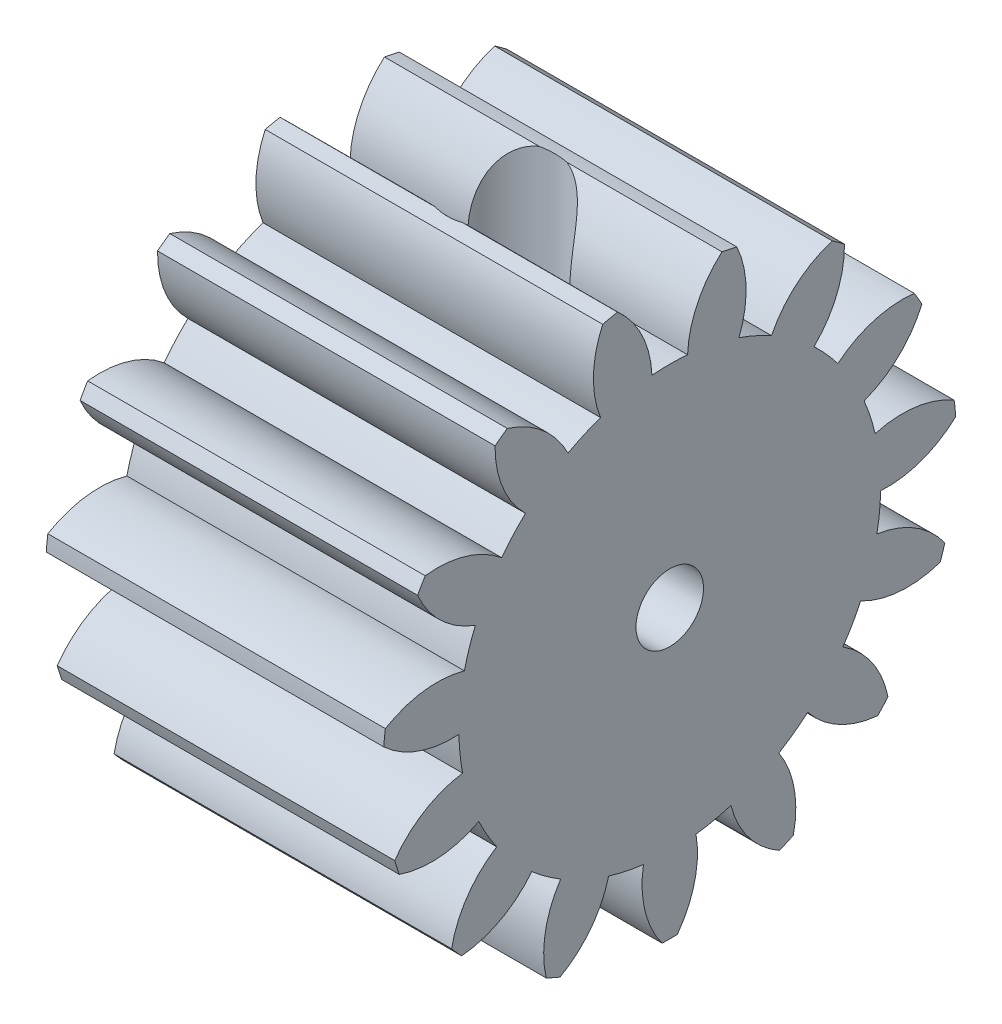
SolidWorks part; units mm, degrees
ref_plane "Plane1" through (0, 0, 0) normal (0, 0, 1) x (1, 0, 0)
ref_plane "Plane2" through (0, 0, 0) normal (0, 1, 0) x (1, 0, 0)
ref_plane "Plane3" through (0, 0, 0) normal (1, 0, 0) x (0, 0, -1)
other "Configuration Table"
sketch "HoldingSke" plane through (0, 0, 0) normal (0, 1, 0) x (1, 0, 0)
  line L0 (0, 0) -> (0.644, -0.1725)
  line L1 (-15, 0) -> (100, 0) construction
  line L2 (0, 0) -> (-2.1039, 2.3779)
  line L3 (0, 0) -> (-11.863, 4.5341)
  line L4 (0, 0) -> (8.3417, 2.2352)
  line L5 (0, 0) -> (-46.8476, -17.4728)
  line L6 (0, 0) -> (-12.4344, -8.3896)
  line L7 (-2.1039, 2.3779) -> (8.6586, 51.2059)
  line L8 (-76.2, 54.61) -> (-75.7, 54.61)
  line L9 (-71.009, 38.7566) -> (-53.1078, 45.2721)
  line L10 (-76.2, 71.12) -> (104.1128, 71.12)
  line L11 (0, 0) -> (-15, 0)
  line L12 (-76.2, 101.6) -> (-76.147, 101.6)
  line L13 (24.9733, 27.94) -> (52.9518, 28.4284)
  line L14 (24.9733, 27.94) -> (24.9743, 27.94)
  line L15 (24.9733, 27.94) -> (100.4006, 29.5858)
  line L16 (-63.627, -1.5) -> (-12.827, -1.5)
  circle A0 centre (0, 0) radius 1.5
  circle A1 centre (0, 0) radius 9.374
  circle A2 centre (0, 0) radius 37.5
  circle A3 centre (0, 0) radius 1.5
  dimension "MHD" = 18.748
  dimension "Hub_dia" = 75
  dimension "Bore" = 3
  dimension "MBD" = 3
  dimension "Num_teeth" = 15
  dimension "Pitch" = 0.6667
  dimension "Overall_len" = 50
  dimension "Show_teeth" = 15
  dimension "Thickness" = 15
  dimension "OAL" = 50.0001
  dimension "T_dim" = 0.5
  dimension "Ap" = 20
  dimension "H" = 19.05
  dimension "Pitch_radius" = 180.3128
  dimension "Width" = 15
  dimension "Backlash" = 0.053
  dimension "Addendum_fac" = 1
  dimension "Dedendum_fac" = 1.25
  dimension "Clearance_fac" = 0.25
  dimension "Dedendum_add" = 0.001
  dimension "Module" = 1.5
sketch "BasProSke" plane through (0, 0, 0) normal (0, 1, 0) x (1, 0, 0)
  line L0 (-10, 0) -> (60, 0) construction
  line L1 (0, 0) -> (0, 12.75)
  line L2 (0, 0) -> (15, 0)
  line L3 (15, 0) -> (15, 12.75)
  line L4 (15, 12.75) -> (0, 12.75)
  dimension "Thickness" = 15
  dimension "Diameter" = 25.5
revolve "Base-Revolve" add sketch "BasProSke" angle 360 about L0
sketch "TooCutSke" plane through (0, 0, 0) normal (1, 0, 0) x (0, 0, -1)
  line L1 (0, 0) -> (0, 107) construction
  line L2 (0, 0) -> (-1.2686, 11.1782) construction
  line L3 (0, 0) -> (-4.6563, 21.9061) construction
  line L4 (-1.2686, 11.1782) -> (-2.3281, 10.953) construction
  arc A0 (0.7915, 9.3405) -> (-0.7915, 9.3405) centre (0, 0) ccw
  arc A1 (2.3447, 12.5584) -> (-2.3447, 12.5584) centre (0, 0) ccw
  circle A2 centre (0, 0) radius 11.25 construction
  circle A3 centre (0, 0) radius 10.5715 construction
  arc A4 (-0.7915, 9.3405) -> (-2.3447, 12.5584) centre (-5.2877, 9.1541) ccw
  arc A5 (2.3447, 12.5584) -> (0.7915, 9.3405) centre (5.2877, 9.1541) ccw
  dimension "Root_dia" = 18.748
  dimension "Overcut_dia" = 25.5508
  dimension "Pitch_dia" = 22.5
  dimension "Base_dia" = 21.1431
  dimension "Flank_rad" = 4.5
  dimension "Half_ang" = 12
  dimension "Half_CT" = 1.0832
extrude "ToothCut" cut sketch "TooCutSke" along normal through all
fillet "Breaks" [suppressed] radius 0.03
fillet "RootFillets" [suppressed] radius 0.376
pattern_circular "TeethCuts" count 15 every 24 about axis through (-10, 0, 0) along (1, 0, 0) of "ToothCut", "RootFillets", "Breaks"
sketch "HubNeaOneSke" plane through (0, 0, 0) normal (-1, 0, 0) x (0, 0, 1)
  circle A0 centre (0, 0) radius 9.374
  dimension "Diameter" = 18.748
extrude "HubNearOne" [suppressed] add sketch "HubNeaOneSke" along normal blind 35.0001
sketch "HubNeaBotSke" plane through (0, 0, 0) normal (-1, 0, 0) x (0, 0, 1)
  circle A0 centre (0, 0) radius 9.374
  dimension "Diameter" = 18.748
extrude "HubNearBoth" [suppressed] add sketch "HubNeaBotSke" along normal blind 17.5
ref_plane "FarPln" through (15, 0, 0) normal (1, 0, 0) x (0, 0, -1)
sketch "HubFarSke" plane through (15, 0, 0) normal (1, 0, 0) x (0, 0, -1)
  circle A0 centre (0, 0) radius 9.374
  dimension "Diameter" = 18.748
extrude "HubFar" [suppressed] add sketch "HubFarSke" along normal blind 17.5
sketch "BorSke" plane through (0, 0, 0) normal (1, 0, 0) x (0, 0, -1)
  circle A0 centre (0, 0) radius 1.5
  dimension "Diameter" = 3
extrude "Bore" cut sketch "BorSke" along normal mid plane 100.0001
sketch "KeySke" plane through (0, 0, 0) normal (1, 0, 0) x (0, 0, -1)
  line L0 (-0.6, 0) -> (-0.6, 2)
  line L1 (-0.6, 2) -> (0.6, 2)
  line L2 (0.6, 2) -> (0.6, 0)
  line L3 (0, 0) -> (0, 34) construction
  line L4 (-0.6, 0) -> (0.6, 0)
  dimension "Offset" = 2
  dimension "Width" = 1.2
extrude "Keyway" [suppressed] cut sketch "KeySke" along normal mid plane 100.0001
pattern_circular "Keyway2" [suppressed] count 2 every 90 about axis through (-10, 0, 0) along (1, 0, 0)
sketch "Sketch1" plane through (0, 0, 0) normal (0, 1, 0) x (1, 0, 0)
  circle A0 centre (7.5, 0) radius 2.4
extrude "Cut-Extrude1" cut sketch "Sketch1" along normal blind 18
equation "' \"Module@HoldingSke\" = 6.35"
equation "' \"Num_teeth@HoldingSke\" = 12"
equation "' \"Ap@HoldingSke\" =  20"
equation "' \"Ap@HoldingSke\" = 20"
equation "' \"Width@HoldingSke\" = 0.5 * 25.4"
equation "' \"Hub_dia@HoldingSke\"= 1 * 25.4"
equation "' \"Hub_dia@HoldingSke\" = 1 * 25.4"
equation "' \"Overall_len@HoldingSke\" = 1.0 * 25.4"
equation "' \"Bore@HoldingSke\" = 0.75 * 25.4"
equation "' \"T_dim@HoldingSke\" = 0.1 * 25.4"
equation "' \"Width@KeySke\" = 0.25 * 25.4"
equation "' \"Show_teeth@HoldingSke\" = 13"
equation "' \"Backlash@HoldingSke\" = 0.009 * 25.4"
equation "' \"Addendum_fac@HoldingSke\" = 1.0"
equation "' \"Dedendum_fac@HoldingSke\" = 1.25"
equation "' \"Dedendum_add@HoldingSke\" = 0.00005 * 25.4"
equation "' \"Clearance_fac@HoldingSke\" = 0.25"
equation "\"Pitch@HoldingSke\" = 1 / \"Module@HoldingSke\""
equation "\"Overcut_dia@TooCutSke\" = (\"Num_teeth@HoldingSke\" + 2 * \"Addendum_fac@HoldingSke\") / \"Pitch@HoldingSke\" + 0.002 * 25.4"
equation "\"Pitch_dia@TooCutSke\" = \"Num_teeth@HoldingSke\" / \"Pitch@HoldingSke\""
equation "\"Base_dia@TooCutSke\" = \"Num_teeth@HoldingSke\" / \"Pitch@HoldingSke\" * cos((\"Ap@HoldingSke\"  * 3.14159265 / 180))"
equation "\"Root_dia@TooCutSke\" = (\"Num_teeth@HoldingSke\" + 2) / \"Pitch@HoldingSke\" - 2 * (\"Addendum_fac@HoldingSke\" + \"Dedendum_fac@HoldingSke\") / \"Pitch@HoldingSke\" - \"Dedendum_add@HoldingSke\" * 2"
equation "\"Half_ang@TooCutSke\" = 180 / \"Num_teeth@HoldingSke\""
equation "\"Half_CT@TooCutSke\" = \"Num_teeth@HoldingSke\" / \"Pitch@HoldingSke\" * sin((3.14159265 / 2 / \"Num_teeth@HoldingSke\")) / 2 - 7 * \"Backlash@HoldingSke\" / 4"
equation "\"Flank_rad@TooCutSke\" = \"Num_teeth@HoldingSke\" / \"Pitch@HoldingSke\" / 5"
equation "\"Radius@RootFillets\" = \"Clearance_fac@HoldingSke\" / \"Pitch@HoldingSke\" + \"Dedendum_add@HoldingSke\""
equation "\"Break_rad@Breaks\" = 0.02 / \"Pitch@HoldingSke\""
equation "\"Thickness@HoldingSke\" = \"Width@HoldingSke\""
equation "\"OAL@HoldingSke\" = \"Thickness@HoldingSke\""
equation "\"MHD@HoldingSke\" = (\"Num_teeth@HoldingSke\" + 2) / \"Pitch@HoldingSke\" - 2 * (\"Addendum_fac@HoldingSke\" + \"Dedendum_fac@HoldingSke\")  / \"Pitch@HoldingSke\" - \"Dedendum_add@HoldingSke\" * 2"
equation "\"MBD@HoldingSke\" = (\"Num_teeth@HoldingSke\" + 2) / \"Pitch@HoldingSke\" - 2 * (\"Addendum_fac@HoldingSke\" + \"Dedendum_fac@HoldingSke\")  / \"Pitch@HoldingSke\" - \"Dedendum_add@HoldingSke\" * 2 - 0.002 * 25.4"
equation "\"MHD@HoldingSke\" = ((sgn( \"MHD@HoldingSke\" - \"Hub_dia@HoldingSke\" )-1)*( \"MHD@HoldingSke\" - \"Hub_dia@HoldingSke\" ))/-2+ \"Hub_dia@HoldingSke\""
equation "\"MBD@HoldingSke\" = ((sgn( \"MBD@HoldingSke\" - \"Bore@HoldingSke\" )-1)*( \"MBD@HoldingSke\" - \"Bore@HoldingSke\" ))/-2+ \"Bore@HoldingSke\""
equation "\"OAL@HoldingSke\" = ((sgn( \"OAL@HoldingSke\" - \"Overall_len@HoldingSke\" )+1)*( \"OAL@HoldingSke\" - \"Overall_len@HoldingSke\" ))/2 + \"Overall_len@HoldingSke\" + 0.000002 * 25.4"
equation "\"Num_teeth@TeethCuts\" = int( \"Show_teeth@HoldingSke\" ) + 1"
equation "\"Num_teeth@TeethCuts\" = ((sgn( \"Num_teeth@TeethCuts\" - \"Num_teeth@HoldingSke\" )-1)*( \"Num_teeth@TeethCuts\" - \"Num_teeth@HoldingSke\" ))/-2+ \"Num_teeth@HoldingSke\""
equation "\"Num_teeth@TeethCuts\" = ((sgn( \"Num_teeth@TeethCuts\" - 2.0)+1)*( \"Num_teeth@TeethCuts\" - 2.0))/2 +2.0"
equation "\"Angle@TeethCuts\" = 360.0 / \"Num_teeth@HoldingSke\""
equation "\"Diameter@BasProSke\" = (\"Num_teeth@HoldingSke\" + 2 * \"Addendum_fac@HoldingSke\") / \"Pitch@HoldingSke\""
equation "\"Thickness@BasProSke\"  = \"Thickness@HoldingSke\""
equation "' \"Fillet_rad@BasProSke\" =  \"Thickness@HoldingSke\" * 0.05"
equation "' \"Fillet_rad@BasProSke\" = \"Thickness@HoldingSke\" * 0.05"
equation "\"MHD@HoldingSke\" = ((sgn( \"MHD@HoldingSke\" - \"Root_dia@TooCutSke\" )-1)*( \"MHD@HoldingSke\" - \"Root_dia@TooCutSke\" ))/-2+ \"Root_dia@TooCutSke\""
equation "\"Diameter@HubNeaOneSke\" = \"MHD@HoldingSke\""
equation "\"Length@HubNearOne\" = \"OAL@HoldingSke\" - \"Thickness@BasProSke\""
equation "\"Diameter@HubNeaBotSke\" = \"MHD@HoldingSke\""
equation "\"Length@HubNearBoth\" = ( \"OAL@HoldingSke\" - \"Thickness@BasProSke\" ) / 2.0"
equation "\"Thickness@FarPln\" = \"Thickness@BasProSke\""
equation "\"Diameter@HubFarSke\" = \"MHD@HoldingSke\""
equation "\"Length@HubFar\" = ( \"OAL@HoldingSke\" - \"Thickness@BasProSke\" ) / 2.0"
equation "\"Diameter@BorSke\" = \"MBD@HoldingSke\""
equation "\"D1@Bore\" = \"OAL@HoldingSke\" * 2.0"
equation "\"D1@Keyway\" = \"OAL@HoldingSke\" * 2.0"
equation "\"Offset@KeySke\" = \"T_dim@HoldingSke\" + \"MBD@HoldingSke\" / 2.0"
